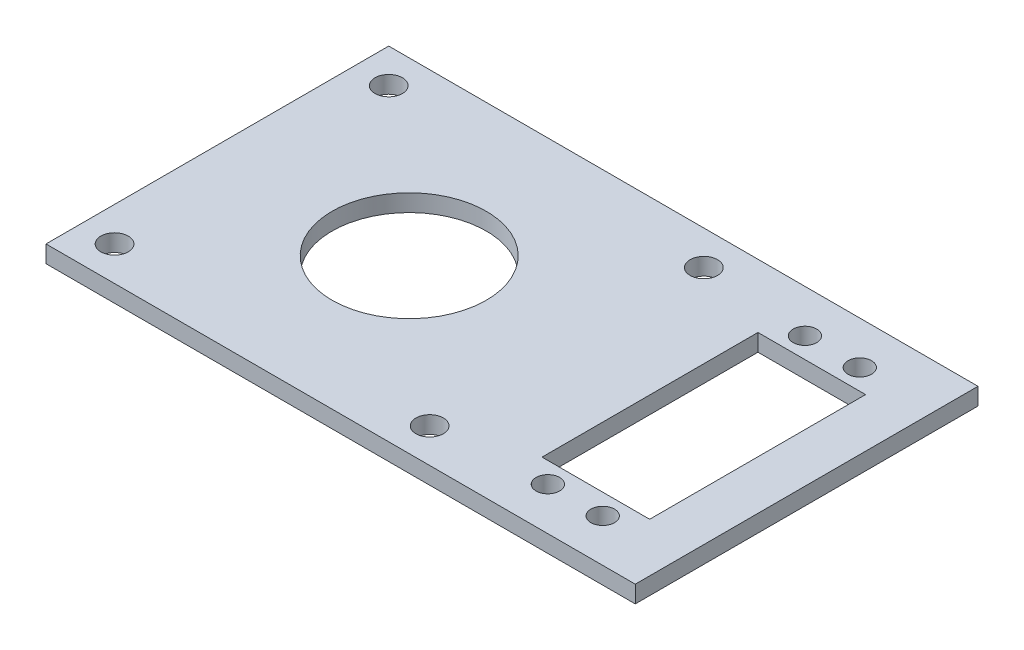
SolidWorks part; units mm, degrees
ref_plane "Front Plane" through (0, 0, 0) normal (0, 0, 1) x (1, 0, 0)
ref_plane "Top Plane" through (0, 0, 0) normal (0, 1, 0) x (1, 0, 0)
ref_plane "Right Plane" through (0, 0, 0) normal (1, 0, 0) x (0, 0, -1)
sketch "Sketch1" plane through (0, 0, 0) normal (0, 1, 0) x (1, 0, 0)
  circle A0 centre (0, 0) radius 4.7625 construction
  circle A1 centre (-44.45, 0) radius 39.6875 construction
  circle A2 centre (-55.5625, 0) radius 50.8 construction
  dimension "D1" = 9.525
  dimension "D2" = 79.375
  dimension "D3" = 101.6
sketch "Sketch2" plane through (0, 0, 0) normal (0, 1, 0) x (1, 0, 0)
  line L0 (0, -10.3505) -> (0, 0) construction
  line L1 (-9.9695, -30.353) -> (9.9695, -30.353)
  line L2 (-9.9695, -30.353) -> (-9.9695, 9.652)
  line L3 (-9.9695, 9.652) -> (9.9695, 9.652)
  line L4 (9.9695, -30.353) -> (9.9695, 9.652)
  line L5 (-9.9695, -30.353) -> (9.9695, 9.652) construction
  line L6 (-9.9695, 9.652) -> (9.9695, -30.353) construction
  line L8 (-5.08, -34.163) -> (5.08, -34.163) construction
  line L9 (-5.08, -34.163) -> (-5.08, 13.462) construction
  line L10 (-5.08, 13.462) -> (5.08, 13.462) construction
  line L11 (5.08, -34.163) -> (5.08, 13.462) construction
  line L12 (-5.08, -34.163) -> (5.08, 13.462) construction
  line L13 (-5.08, 13.462) -> (5.08, -34.163) construction
  line L14 (19.05, 21.3995) -> (-19.05, 21.3995)
  line L15 (19.05, 21.3995) -> (19.05, -42.1005)
  line L16 (19.05, -42.1005) -> (-19.05, -42.1005)
  line L17 (-19.05, 21.3995) -> (-19.05, -42.1005)
  circle A0 centre (5.08, 13.462) radius 2.1844
  circle A1 centre (-5.08, 13.462) radius 2.1844
  circle A2 centre (-5.08, -34.163) radius 2.1844
  circle A3 centre (5.08, -34.163) radius 2.1844
  point P0 (0, -10.3505)
  dimension "D6" = 4.3688
  dimension "D1" = 9.652
  dimension "D2" = 19.939
  dimension "D3" = 40.005
  dimension "D4" = 10.16
  dimension "D5" = 13.462
  dimension "D7" = 31.75
  dimension "D8" = 31.75
  dimension "D9" = 19.05
  dimension "D10" = 19.05
extrude "Boss-Extrude1" add sketch "Sketch2" along normal blind 3.175
sketch "Sketch3" [suppressed] plane through (0, 3.175, 0) normal (0, 1, 0) x (1, 0, 0)
  line L0 (9.9695, -10.3505) -> (-43.2281, -10.3505) construction
  line L1 (9.9695, -30.353) -> (9.9695, 9.652) construction
  line L2 (-67.4062, 21.3995) -> (-19.05, -42.1005) construction
  line L3 (-19.05, 21.3995) -> (-67.4062, 21.3995)
  line L4 (-19.05, 21.3995) -> (-19.05, -42.1005)
  line L5 (-19.05, -42.1005) -> (-67.4062, -42.1005)
  line L6 (-67.4062, 21.3995) -> (-67.4062, -42.1005)
  line L7 (-19.05, -42.1005) -> (-19.3924, -41.8672) construction
  line L8 (-25.4, 15.0495) -> (-61.0562, 15.0495) construction
  line L9 (-61.0562, 15.0495) -> (-61.0562, -35.7505) construction
  line L10 (-25.4, -35.7505) -> (-61.0562, -35.7505) construction
  line L11 (-25.4, 15.0495) -> (-25.4, -35.7505) construction
  circle A0 centre (-43.2281, -10.3505) radius 39.6875 construction
  circle A1 centre (0, 0) radius 4.7625 construction
  circle A2 centre (-44.45, 0) radius 39.6875 construction
  circle A3 centre (-43.2281, -10.3505) radius 14.2875
  circle A4 centre (-61.0562, 15.0495) radius 2.54
  circle A5 centre (-25.4, 15.0495) radius 2.54
  circle A6 centre (-25.4, -35.7505) radius 2.54
  circle A7 centre (-61.0562, -35.7505) radius 2.54
  dimension "D1" = 28.575
  dimension "D3" = 5.08
  dimension "D2" = 6.35
extrude "Boss-Extrude2" [suppressed] add sketch "Sketch3" against normal through all
sketch "Sketch4" plane through (0, 3.175, 0) normal (0, 1, 0) x (1, 0, 0)
  line L0 (9.9695, -10.3505) -> (-54.5899, -10.3505) construction
  line L1 (9.9695, -30.353) -> (9.9695, 9.652) construction
  line L2 (-83.7798, 15.0495) -> (-25.4, 15.0495) construction
  line L3 (-90.1298, -42.1005) -> (-19.05, -42.1005)
  line L4 (-90.1298, -42.1005) -> (-90.1298, 21.3995)
  line L5 (-90.1298, 21.3995) -> (-19.05, 21.3995)
  line L6 (-19.05, -42.1005) -> (-19.05, 21.3995)
  line L7 (-90.1298, -42.1005) -> (-19.05, 21.3995) construction
  line L8 (-90.1298, 21.3995) -> (-19.05, -42.1005) construction
  line L9 (-25.4, -35.7505) -> (-25.4, 15.0495) construction
  line L10 (-83.7798, -35.7505) -> (-25.4, -35.7505) construction
  line L11 (-83.7798, -35.7505) -> (-83.7798, 15.0495) construction
  circle A0 centre (-54.5899, -10.3505) radius 50.8 construction
  circle A1 centre (0, 0) radius 4.7625 construction
  circle A2 centre (-55.5625, 0) radius 50.8 construction
  circle A3 centre (-54.5899, -10.3505) radius 14.2875
  circle A4 centre (-83.7798, 15.0495) radius 2.54
  circle A5 centre (-25.4, 15.0495) radius 2.54
  circle A6 centre (-25.4, -35.7505) radius 2.54
  circle A7 centre (-83.7798, -35.7505) radius 2.54
  dimension "D1" = 28.575
  dimension "D3" = 5.08
  dimension "D2" = 6.35
extrude "Boss-Extrude3" add sketch "Sketch4" against normal through all
